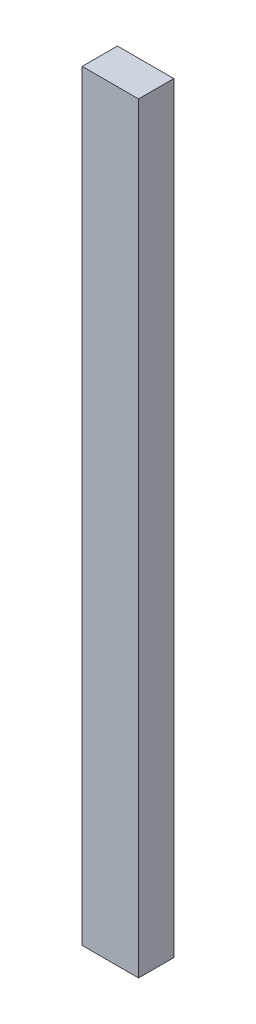
SolidWorks part; units mm, degrees
ref_plane "Plan de face" through (0, 0, 0) normal (0, 0, 1) x (1, 0, 0)
ref_plane "Plan de dessus" through (0, 0, 0) normal (0, 1, 0) x (1, 0, 0)
ref_plane "Plan de droite" through (0, 0, 0) normal (1, 0, 0) x (0, 0, -1)
sketch "Esquisse1" plane through (0, 0, 0) normal (0, 0, 1) x (1, 0, 0)
  line L1 (0, 0) -> (40, 0)
  line L2 (0, 0) -> (0, 540)
  line L3 (0, 540) -> (40, 540)
  line L4 (40, 0) -> (40, 540)
  dimension "D1" = 40
  dimension "D2" = 540
extrude "Boss.-Extru.1" add sketch "Esquisse1" along normal blind 25
